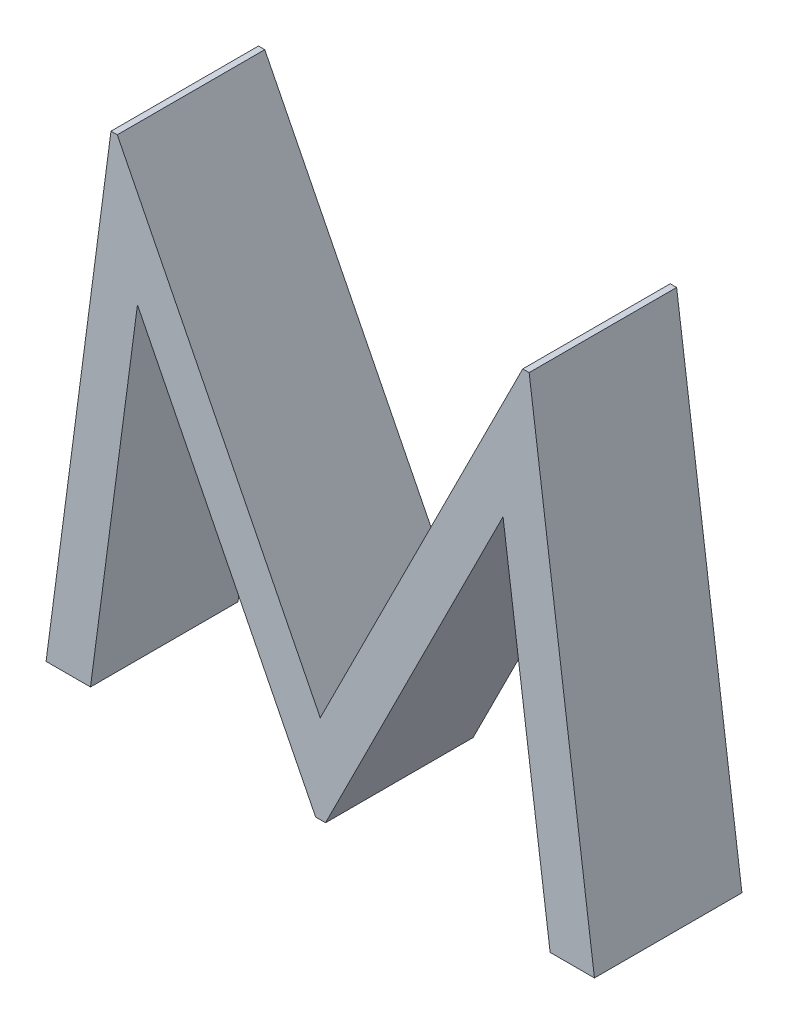
SolidWorks part; units mm, degrees
ref_plane "Plan de face" through (0, 0, 0) normal (0, 0, 1) x (1, 0, 0)
ref_plane "Plan de dessus" through (0, 0, 0) normal (0, 1, 0) x (1, 0, 0)
ref_plane "Plan de droite" through (0, 0, 0) normal (1, 0, 0) x (0, 0, -1)
sketch "Esquisse1" plane through (0, 0, 0) normal (0, 0, 1) x (1, 0, 0)
  text T0 "M" font "Century Gothic" height 5
extrude "Boss.-Extru.1" add sketch "Esquisse1" along normal blind 1.5
